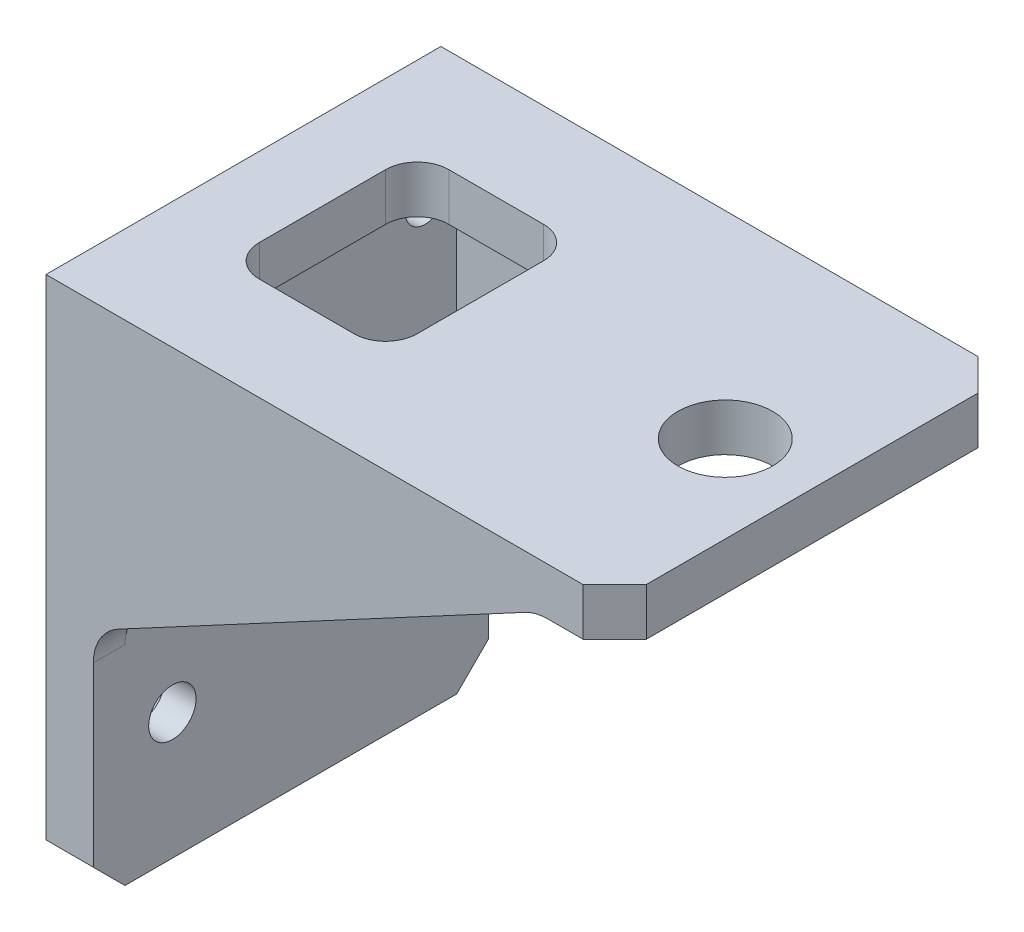
SolidWorks part; units mm, degrees
material "6061-T6 (SS)"
ref_plane "前视基准面" through (0, 0, 0) normal (0, 0, 1) x (1, 0, 0)
ref_plane "上视基准面" through (0, 0, 0) normal (0, 1, 0) x (1, 0, 0)
ref_plane "右视基准面" through (0, 0, 0) normal (1, 0, 0) x (0, 0, -1)
sketch "草图1" plane through (0, 0, 0) normal (0, 0, 1) x (1, 0, 0)
  line L0 (3, 30) -> (36, 30)
  line L1 (0, 0) -> (3, 0)
  line L2 (0, 0) -> (0, 33)
  line L4 (3, 0) -> (3, 30)
  line L5 (36, 30) -> (36, 33)
  line L6 (36, 33) -> (0, 33)
  dimension "D1" = 3
  dimension "D2" = 3
  dimension "D3" = 33
  dimension "D4" = 36
extrude "凸台-拉伸1" add sketch "草图1" along normal blind 25
sketch "草图2" plane through (0, 0, 0) normal (-1, 0, 0) x (0, 0, 1)
  line L0 (12.5, 0) -> (12.5, 13) construction
  line L1 (25, 0) -> (0, 0) construction
  line L2 (12.5, 18) -> (12.5, 28) construction
  line L3 (5, 18) -> (20, 18) construction
  line L4 (5, 18) -> (5, 8) construction
  line L5 (5, 8) -> (20, 8) construction
  line L6 (20, 18) -> (20, 8) construction
  line L7 (5, 18) -> (20, 8) construction
  line L8 (5, 8) -> (20, 18) construction
  line L9 (4, 28) -> (21, 28) construction
  circle A0 centre (5, 18) radius 1.5
  circle A1 centre (20, 18) radius 1.5
  circle A2 centre (20, 8) radius 1.5
  circle A3 centre (5, 8) radius 1.5
  circle A4 centre (4, 28) radius 1.5 construction
  circle A5 centre (21, 28) radius 1.5 construction
  point P17 (12.5, 28)
  dimension "D1" = 3
  dimension "D5" = 3
  dimension "D2" = 10
  dimension "D3" = 15
  dimension "D4" = 13
  dimension "D6" = 17
  dimension "D7" = 28
extrude "切除-拉伸1" cut sketch "草图2" against normal through all
hole_wizard "M3 螺纹孔1" positions "3D草图1" profile "草图4" tap size "M3" standard "ISO" end condition up to next
sketch3d "3D草图1"
  point P0 (0, 28, 4)
  point P3 (0, 28, 21)
sketch "草图4" plane through (0, 28, 4) normal (0, 1, 0) x (0, 0, 1)
  line L0 (0, 0) -> (0, 3)
  line L1 (0, 3) -> (1.25, 3)
  line L2 (1.25, 3) -> (1.25, 0)
  line L5 (1.25, 0) -> (0, 0)
  line L11 (0, -6.35) -> (0, 107.95) construction
  dimension "通孔螺纹孔钻头直径" = 2.5
  dimension "通孔螺纹孔钻头深度" = 3
cosmetic thread "孔螺蚊线1" parameters "D2"=3
cosmetic thread "孔螺蚊线2" parameters "D2"=3
chamfer "倒角1" distance 1 angle 45 2 edges at (0, 8, 21.5) (0, 8, 6.5)
sketch "草图5" plane through (0, 33, 0) normal (0, 1, 0) x (1, 0, 0)
  line L0 (0, -12.5) -> (30.5, -12.5) construction
  line L1 (0, -25) -> (0, 0) construction
  circle A0 centre (30.5, -12.5) radius 3
  dimension "D1" = 30.5
  dimension "D2" = 6
extrude "切除-拉伸2" cut sketch "草图5" against normal blind 25
sketch "草图6" plane through (0, 33, 0) normal (0, 1, 0) x (1, 0, 0)
  line L0 (0, -12.5) -> (10, -12.5) construction
  line L1 (0, -25) -> (0, 0) construction
  line L3 (5, -6.5) -> (15, -6.5)
  line L4 (5, -6.5) -> (5, -18.5)
  line L5 (5, -18.5) -> (15, -18.5)
  line L6 (15, -6.5) -> (15, -18.5)
  line L7 (5, -6.5) -> (15, -18.5) construction
  line L8 (5, -18.5) -> (15, -6.5) construction
  dimension "D1" = 5
  dimension "D2" = 10
  dimension "D3" = 12
extrude "切除-拉伸3" cut sketch "草图6" against normal up to next
fillet "圆角1" radius 2 4 edges at (5, 31.5, 18.5) (15, 31.5, 18.5) (15, 31.5, 6.5) (5, 31.5, 6.5)
chamfer "倒角2" distance 2 angle 45 4 edges at (1.5, 0, 0) (1.5, 0, 25) (36, 31.5, 0) (36, 31.5, 25)
sketch "草图7" plane through (0, 0, 25) normal (0, 0, 1) x (1, 0, 0)
  line L0 (3, 15) -> (31, 30)
  line L2 (3, 2) -> (3, 30) construction
  line L3 (3, 30) -> (34, 30) construction
  dimension "D1" = 28
  dimension "D2" = 15
rib "筋2" sketch "草图7" sketch "草图7" thickness 2 extrusion direction parallel to sketch draft on no parameters "D1"=2
sketch "草图8" plane through (0, 0, 0) normal (0, 0, -1) x (-1, 0, 0)
  line L0 (-3, 15) -> (-31, 30) construction
  line L1 (-3, 15) -> (-31, 30)
rib "筋3" sketch "草图8" sketch "草图8" thickness 2 extrusion direction parallel to sketch draft on no parameters "D1"=2
fillet "圆角2" radius 2 2 edges at (17, 30, 2) (17, 30, 23)
fillet "圆角3" radius 3 4 edges at (31, 30, 2) (31, 30, 23) (3, 15, 24) (3, 15, 1)
